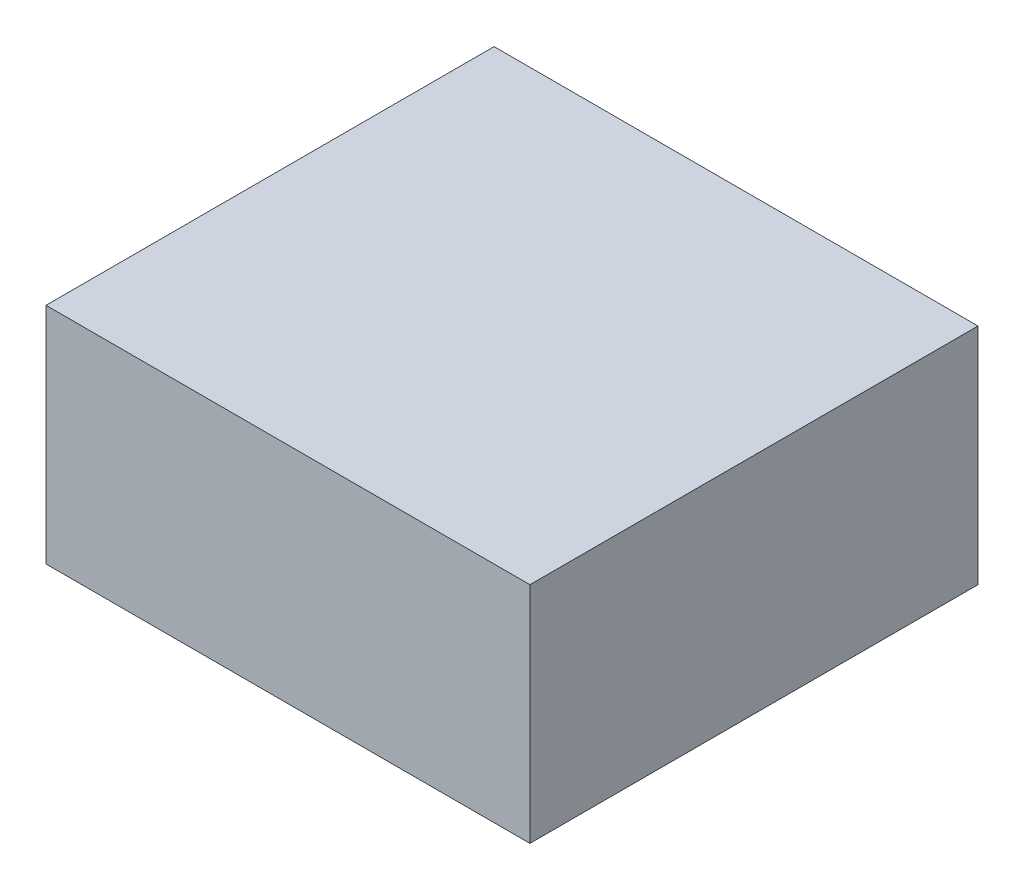
SolidWorks part; units mm, degrees
ref_plane "Front Plane" through (0, 0, 0) normal (0, 0, 1) x (1, 0, 0)
ref_plane "Top Plane" through (0, 0, 0) normal (0, 1, 0) x (1, 0, 0)
ref_plane "Right Plane" through (0, 0, 0) normal (1, 0, 0) x (0, 0, -1)
other "Configuration Table"
sketch "Sketch1" plane through (0, 0, 0) normal (0, 0, 1) x (1, 0, 0)
  line L1 (80, 150) -> (620, 150)
  line L2 (80, 150) -> (80, 400)
  line L3 (80, 400) -> (620, 400)
  line L4 (620, 150) -> (620, 400)
extrude "PRESS_PZP400_motor_rezistans_govdesi_1" add sketch "Sketch1" against normal blind 500 from offset 250 separate body
